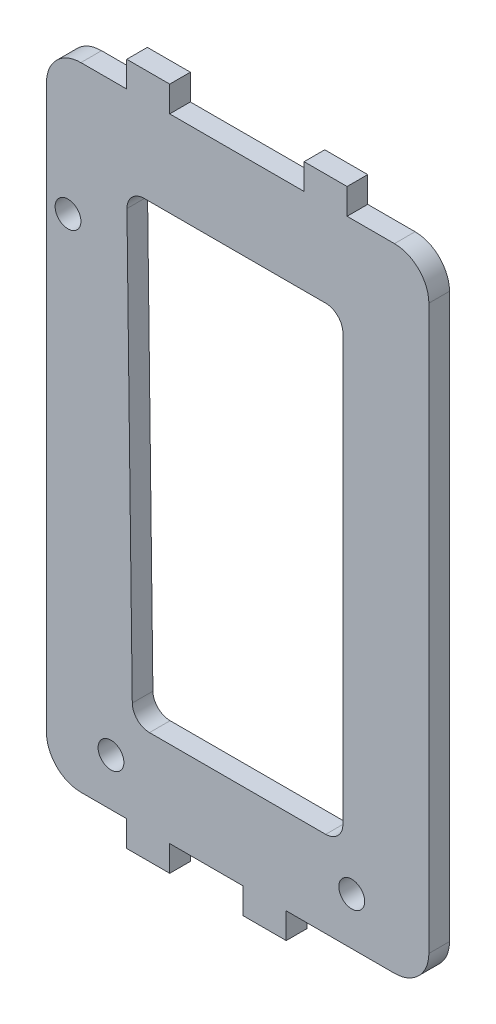
SolidWorks part; units mm, degrees
ref_plane "Alzado" through (0, 0, 0) normal (0, 0, 1) x (1, 0, 0)
ref_plane "Planta" through (0, 0, 0) normal (0, 1, 0) x (1, 0, 0)
ref_plane "Vista lateral" through (0, 0, 0) normal (1, 0, 0) x (0, 0, -1)
sketch "Croquis1" plane through (0, 0, 0) normal (0, 0, 1) x (1, 0, 0)
  line L0 (-27.7352, 52.6459) -> (-43.3652, 52.6459)
  line L1 (-48.3652, -20.8541) -> (-48.3652, -23.8541)
  line L2 (-48.3652, -23.8541) -> (-43.3652, -23.8541)
  line L3 (-43.3652, -23.8541) -> (-43.3652, -20.8541)
  line L4 (-34.8152, -23.8541) -> (-34.8152, -20.8541)
  line L5 (-34.8152, -20.8541) -> (-43.3652, -20.8541)
  line L6 (-57.6952, 48.6459) -> (-57.6952, -16.8541)
  line L8 (-34.8152, -23.8541) -> (-29.8152, -23.8541)
  line L9 (-29.8152, -23.8541) -> (-29.8152, -20.8541)
  line L10 (-29.8152, -20.8541) -> (-17.2252, -20.8541)
  line L12 (-27.7352, 55.6459) -> (-22.7352, 55.6459)
  line L13 (-48.3652, -20.8541) -> (-53.6952, -20.8541)
  line L14 (-13.2252, 48.6459) -> (-13.2252, -16.8541)
  line L16 (-22.7352, 55.6459) -> (-22.7352, 52.6459)
  line L17 (-27.7352, 55.6459) -> (-27.7352, 52.6459)
  line L18 (-22.7352, 52.6459) -> (-17.2252, 52.6459)
  line L20 (-35.5502, 42.6459) -> (-25.2252, 42.6459)
  line L21 (-23.2252, 40.6459) -> (-23.2252, -8.8541)
  line L22 (-25.2252, -10.8541) -> (-45.7201, -10.8541)
  line L23 (-47.7199, -8.8792) -> (-48.3399, 40.6208)
  line L24 (-46.34, 42.6459) -> (-35.5502, 42.6459)
  line L27 (-53.6952, 52.6459) -> (-48.3652, 52.6459)
  line L28 (-48.3652, 52.6459) -> (-48.3652, 55.6459)
  line L29 (-48.3652, 55.6459) -> (-43.3652, 55.6459)
  line L30 (-43.3652, 55.6459) -> (-43.3652, 52.6459)
  arc A0 (-53.6952, -20.8541) -> (-57.6952, -16.8541) centre (-53.6952, -16.8541) cw
  arc A1 (-13.2252, -16.8541) -> (-17.2252, -20.8541) centre (-17.2252, -16.8541) cw
  arc A2 (-17.2252, 52.6459) -> (-13.2252, 48.6459) centre (-17.2252, 48.6459) cw
  arc A3 (-57.6952, 48.6459) -> (-53.6952, 52.6459) centre (-53.6952, 48.6459) cw
  arc A4 (-23.2252, -8.8541) -> (-25.2252, -10.8541) centre (-25.2252, -8.8541) cw
  arc A5 (-25.2252, 42.6459) -> (-23.2252, 40.6459) centre (-25.2252, 40.6459) cw
  arc A6 (-48.3399, 40.6208) -> (-46.34, 42.6459) centre (-46.34, 40.6459) cw
  arc A7 (-45.7201, -10.8541) -> (-47.7199, -8.8792) centre (-45.7201, -8.8541) cw
  circle A8 centre (-55.1952, 36.6459) radius 1.5
  circle A9 centre (-50.1952, -15.3541) radius 1.5
  circle A10 centre (-22.1952, -15.3541) radius 1.5
  point P47 (-8.5252, 49.1459)
  dimension "D1" = 4
  dimension "D2" = 2
extrude "Saliente-Extruir1" add sketch "Croquis1" along normal blind 2.4
